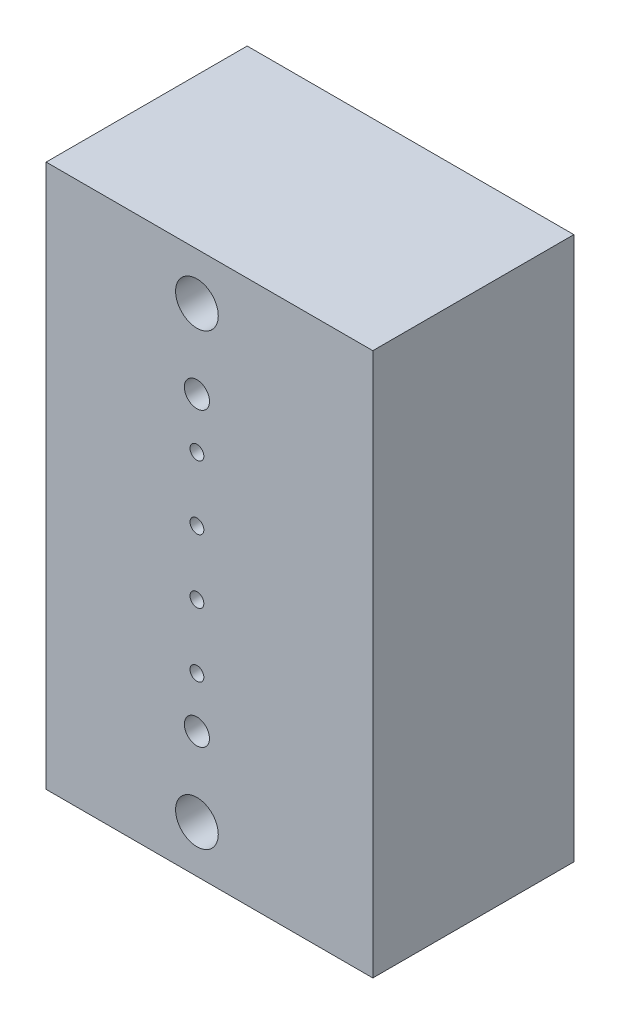
SolidWorks part; units mm, degrees
material "ABS"
ref_plane "Front Plane" through (0, 0, 0) normal (0, 0, 1) x (1, 0, 0)
ref_plane "Top Plane" through (0, 0, 0) normal (0, 1, 0) x (1, 0, 0)
ref_plane "Right Plane" through (0, 0, 0) normal (1, 0, 0) x (0, 0, -1)
sketch "Sketch1" plane through (0, 0, 0) normal (0, 0, 1) x (1, 0, 0)
  line L0 (-4, -16.62) -> (22, -16.62)
  line L1 (22, -16.62) -> (22, 26.62)
  line L2 (22, 26.62) -> (-4, 26.62)
  line L3 (-4, 26.62) -> (-4, -16.62)
  dimension "D1" = 26
  dimension "D2" = 43.24
extrude "Boss-Extrude1" add sketch "Sketch1" along normal blind 16
sketch "Sketch2" plane through (0, 0, 0) normal (0, 0, 1) x (1, 0, 0)
  circle A0 centre (8, -2.62) radius 0.55
  circle A1 centre (8, 2.46) radius 0.55
  circle A2 centre (8, 7.54) radius 0.55
  circle A3 centre (8, 12.62) radius 0.55
  circle A4 centre (8, -12.87) radius 1.7
  circle A5 centre (8, 22.87) radius 1.7
  dimension "D1" = 1.1
  dimension "D2" = 3.4
extrude "Cut-Extrude1" cut sketch "Sketch2" against normal through all and the other way through all
sketch "Sketch3" plane through (0, 0, 0) normal (0, 0, 1) x (1, 0, 0)
  line L0 (-4, -5.12) -> (10.5, -5.12)
  line L1 (10.5, -5.12) -> (10.5, 15.12)
  line L2 (10.5, 15.12) -> (-4, 15.12)
  line L3 (-4, 15.12) -> (-4, -5.12)
extrude "Cut-Extrude3" cut sketch "Sketch3" along normal blind 4
ref_plane "Plane1" through (0, 0, 16) normal (0, 0, 1) x (1, 0, 0)
sketch "Sketch4" plane through (0, 0, 16) normal (0, 0, 1) x (1, 0, 0)
  circle A0 centre (8, -6.62) radius 1
  circle A1 centre (8, 16.62) radius 1
extrude "Cut-Extrude5" cut sketch "Sketch4" against normal blind 10
